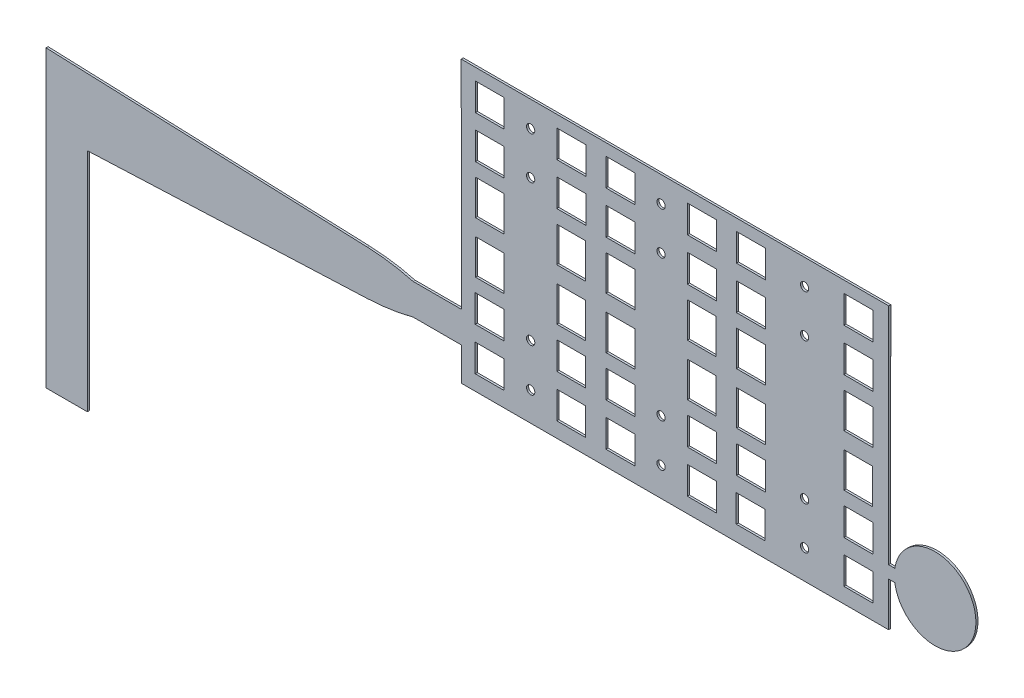
SolidWorks part; units mm, degrees
ref_plane "Alzado" through (0, 0, 0) normal (0, 0, 1) x (1, 0, 0)
ref_plane "Planta" through (0, 0, 0) normal (0, 1, 0) x (1, 0, 0)
ref_plane "Vista lateral" through (0, 0, 0) normal (1, 0, 0) x (0, 0, -1)
sketch "Model" plane through (0, 0, 0) normal (0, 0, 1) x (1, 0, 0)
  line L0 (63.6574, 52.8342) -> (70.6033, 52.8342)
  line L1 (83.3266, 52.8342) -> (90.3731, 52.8342)
  line L16 (63.6033, 8.4929) -> (63.6033, 1.862)
  line L18 (70.6033, 8.4929) -> (70.6033, 1.862)
  line L20 (63.6033, -1.862) -> (63.6033, -8.4929)
  line L22 (70.6033, -1.862) -> (70.6033, -8.4929)
  line L23 (114.8871, 52.902) -> (121.9188, 52.902)
  line L25 (90.3266, 8.4929) -> (90.3266, 1.862)
  line L27 (126.7514, 46.2379) -> (133.7301, 46.2379)
  line L31 (152.7437, 52.902) -> (159.7495, 52.902)
  line L32 (-40.1542, 7.8736) -> (-40.1542, -8.6736)
  line L33 (-40.1542, -8.6736) -> (-40.1542, -63.3381)
  line L35 (-40.1542, -63.3381) -> (-30.1542, -63.3381)
  line L36 (-30.1542, -63.3381) -> (-30.1542, -8.6736)
  line L38 (159.7495, 46.2379) -> (152.7437, 46.2379)
  line L39 (60.2582, -12.1607) -> (163.5406, -12.124)
  line L41 (83.3266, 8.4929) -> (83.3266, 1.862)
  line L43 (90.3266, -1.862) -> (90.3266, -8.4929)
  line L45 (83.3266, -1.862) -> (83.3266, -8.4929)
  line L47 (60.2286, 55.7055) -> (163.5735, 55.7055)
  line L48 (60.2286, 55.7055) -> (60.2582, 3.3361)
  line L49 (60.2582, -4.1361) -> (60.2582, -12.1607)
  line L50 (152.7437, 42.5548) -> (159.7495, 42.5548)
  line L51 (37.5383, -5.7873) -> (-30.1542, -8.6736)
  line L52 (-40.1542, 7.8736) -> (37.5383, 4.9873)
  line L53 (159.7495, 35.8907) -> (152.7437, 35.8907)
  line L54 (133.7301, 42.5548) -> (126.7354, 42.5548)
  line L55 (126.7354, 35.8907) -> (133.7301, 35.8907)
  line L56 (121.895, 35.9097) -> (114.8871, 35.9097)
  line L57 (114.8871, 42.5853) -> (121.895, 42.5853)
  line L58 (95.1895, 42.5853) -> (102.1795, 42.5853)
  line L59 (102.1795, 46.2074) -> (95.2023, 46.2074)
  line L60 (90.3731, 46.2049) -> (83.3266, 46.2049)
  line L61 (95.1795, 8.4893) -> (95.1795, 1.8233)
  line L63 (83.3266, 42.5878) -> (90.3731, 42.5878)
  line L64 (102.1795, 8.4893) -> (102.1795, 1.8233)
  line L66 (95.1795, -1.8233) -> (95.1795, -8.4893)
  line L68 (90.3731, 35.9585) -> (83.3266, 35.9585)
  line L69 (102.1795, -1.8233) -> (102.1795, -8.4893)
  line L71 (121.8871, -1.8233) -> (121.8871, -8.4893)
  line L73 (114.8871, -1.8233) -> (114.8871, -8.4893)
  line L75 (63.6574, 42.5878) -> (70.6033, 42.5878)
  line L76 (70.6033, 46.2049) -> (63.6574, 46.2049)
  line L77 (63.6033, 8.4929) -> (70.6033, 8.4929)
  line L78 (83.3266, 8.4929) -> (90.3266, 8.4929)
  line L79 (95.1795, 8.4893) -> (102.1795, 8.4893)
  line L80 (126.7301, 8.4673) -> (133.7301, 8.4673)
  line L81 (152.7437, 8.4673) -> (159.7437, 8.4673)
  line L82 (159.7437, 1.7882) -> (152.7437, 1.7882)
  line L83 (133.7301, 1.7882) -> (126.7301, 1.7882)
  line L84 (121.8871, 1.8233) -> (114.8871, 1.8233)
  line L85 (102.1795, 1.8233) -> (95.1795, 1.8233)
  line L86 (90.3266, 1.862) -> (83.3266, 1.862)
  line L87 (70.6033, 1.862) -> (63.6033, 1.862)
  line L88 (63.6033, -1.862) -> (70.6033, -1.862)
  line L89 (83.3266, -1.862) -> (90.3266, -1.862)
  line L91 (121.8871, 8.4893) -> (114.8871, 8.4893)
  line L92 (114.8871, 1.8233) -> (114.8871, 8.4893)
  line L94 (126.7301, 8.4673) -> (126.7301, 1.7882)
  line L99 (48.5942, 3.3361) -> (60.2582, 3.3361)
  line L100 (48.5942, -4.1361) -> (60.2582, -4.1361)
  line L101 (133.7301, 8.4673) -> (133.7301, 1.7882)
  line L113 (95.1795, -1.8233) -> (102.1795, -1.8233)
  line L114 (121.8871, 8.4893) -> (121.8871, 1.8233)
  line L123 (126.7038, -1.819) -> (126.7038, -8.4359)
  line L126 (159.729, -1.819) -> (159.729, -8.4359)
  line L128 (159.7437, 1.7882) -> (159.7437, 8.4673)
  line L132 (159.7495, 52.902) -> (159.7495, 46.2379)
  line L147 (133.7038, -1.819) -> (133.7038, -8.4359)
  line L151 (152.729, -8.4359) -> (152.729, -1.819)
  line L152 (114.8871, -1.8233) -> (121.8871, -1.8233)
  line L156 (152.7437, 1.7882) -> (152.7437, 8.4673)
  line L157 (126.7354, 52.902) -> (126.7354, 46.2379)
  line L159 (126.7354, 42.5548) -> (126.7354, 35.8907)
  line L161 (159.7495, 42.5548) -> (159.7495, 35.8907)
  line L164 (121.895, 35.9097) -> (121.895, 42.5853)
  line L166 (95.1895, 35.9097) -> (95.1895, 42.5853)
  line L168 (95.1895, 46.2074) -> (95.1895, 52.902)
  line L172 (63.6574, 52.8342) -> (63.6574, 46.2049)
  line L174 (70.6033, 52.8342) -> (70.6033, 46.2049)
  line L176 (63.6574, 42.5878) -> (63.6574, 35.9533)
  line L180 (90.3731, 52.8342) -> (90.3731, 46.2049)
  line L182 (90.3731, 42.5878) -> (90.3731, 35.9585)
  line L185 (63.6574, 35.9533) -> (70.6033, 35.9533)
  line L186 (70.6033, 42.5878) -> (70.6033, 35.9533)
  line L190 (83.3266, 35.9585) -> (83.3266, 42.5878)
  line L194 (126.7038, -1.819) -> (133.7038, -1.819)
  line L195 (83.3266, 46.2049) -> (83.3266, 52.8342)
  line L196 (95.2023, 52.8584) -> (102.1795, 52.8584)
  line L197 (95.2023, 52.8584) -> (95.2023, 46.2074)
  line L199 (102.1795, 52.8584) -> (102.1795, 46.2074)
  line L202 (95.1895, 35.9097) -> (102.1795, 35.9097)
  line L203 (152.729, -1.819) -> (159.729, -1.819)
  line L204 (102.1795, 42.5853) -> (102.1795, 35.9097)
  line L208 (114.8871, 35.9097) -> (114.8871, 42.5853)
  line L209 (121.9188, 46.2351) -> (114.8871, 46.2351)
  line L210 (121.9188, 46.2351) -> (121.9188, 52.902)
  line L212 (114.8871, 46.2351) -> (114.8871, 52.902)
  line L213 (126.7514, 52.8864) -> (133.7301, 52.8864)
  line L214 (126.7514, 52.8864) -> (126.7514, 46.2379)
  line L216 (133.7301, 52.8864) -> (133.7301, 46.2379)
  line L220 (133.7301, 42.5548) -> (133.7301, 35.8907)
  line L224 (152.7437, 35.8907) -> (152.7437, 42.5548)
  line L228 (152.7437, 46.2379) -> (152.7437, 52.902)
  line L229 (63.6719, 32.7054) -> (70.6033, 32.7054)
  line L230 (63.6719, 32.7054) -> (63.6719, 24.2109)
  line L231 (63.6719, 24.2109) -> (70.6033, 24.2109)
  line L232 (70.6033, 32.7054) -> (70.6033, 24.2109)
  line L233 (63.7086, 20.254) -> (70.6033, 20.254)
  line L234 (63.7086, 20.254) -> (63.7086, 11.7587)
  line L235 (63.7086, 11.7587) -> (70.6033, 11.7587)
  line L236 (70.6033, 20.254) -> (70.6033, 11.7587)
  line L237 (90.3114, 11.7467) -> (83.3266, 11.7467)
  line L238 (90.3114, 11.7467) -> (90.3114, 20.2401)
  line L239 (90.3114, 20.2401) -> (83.3266, 20.2401)
  line L240 (83.3266, 11.7467) -> (83.3266, 20.2401)
  line L241 (90.2656, 24.1969) -> (83.3266, 24.1969)
  line L242 (90.2656, 24.1969) -> (90.2656, 32.6894)
  line L243 (90.2656, 32.6894) -> (83.3266, 32.6894)
  line L244 (83.3266, 24.1969) -> (83.3266, 32.6894)
  line L245 (159.729, -8.4359) -> (152.729, -8.4359)
  line L246 (95.2169, 32.6805) -> (102.1795, 32.6805)
  line L247 (95.2169, 32.6805) -> (95.2169, 24.1873)
  line L248 (95.2169, 24.1873) -> (102.1795, 24.1873)
  line L249 (102.1795, 32.6805) -> (102.1795, 24.1873)
  line L250 (121.8739, 32.6569) -> (114.8871, 32.6569)
  line L251 (121.8739, 32.6569) -> (121.8739, 24.1766)
  line L252 (121.8739, 24.1766) -> (114.8871, 24.1766)
  line L253 (114.8871, 32.6569) -> (114.8871, 24.1766)
  line L254 (121.813, 20.2091) -> (114.8871, 20.2091)
  line L255 (121.813, 20.2091) -> (121.813, 11.729)
  line L256 (121.813, 11.729) -> (114.8871, 11.729)
  line L257 (114.8871, 20.2091) -> (114.8871, 11.729)
  line L258 (95.2605, 20.2314) -> (102.1795, 20.2314)
  line L259 (95.2605, 20.2314) -> (95.2605, 11.7381)
  line L260 (95.2605, 11.7381) -> (102.1795, 11.7381)
  line L261 (102.1795, 20.2314) -> (102.1795, 11.7381)
  line L262 (126.8116, 20.2054) -> (133.7301, 20.2054)
  line L263 (126.8116, 20.2054) -> (126.8116, 11.7157)
  line L264 (126.8116, 11.7157) -> (133.7301, 11.7157)
  line L268 (133.7301, 20.2054) -> (133.7301, 11.7157)
  line L269 (126.7675, 32.6533) -> (133.7301, 32.6533)
  line L270 (126.7675, 32.6533) -> (126.7675, 24.1624)
  line L271 (126.7675, 24.1624) -> (133.7301, 24.1624)
  line L272 (133.7301, 32.6533) -> (133.7301, 24.1624)
  line L273 (159.7336, 32.6369) -> (152.7437, 32.6369)
  line L274 (159.7336, 32.6369) -> (159.7336, 24.1492)
  line L275 (159.7336, 24.1492) -> (152.7437, 24.1492)
  line L276 (152.7437, 32.6369) -> (152.7437, 24.1492)
  line L277 (159.6767, 20.1824) -> (152.7437, 20.1824)
  line L278 (159.6767, 20.1824) -> (159.6767, 11.7002)
  line L279 (159.6767, 11.7002) -> (152.7437, 11.7002)
  line L280 (152.7437, 20.1824) -> (152.7437, 11.7002)
  line L281 (133.7038, -8.4359) -> (126.7038, -8.4359)
  line L282 (121.8871, -8.4893) -> (114.8871, -8.4893)
  line L283 (102.1795, -8.4893) -> (95.1795, -8.4893)
  line L284 (70.6033, -8.4929) -> (63.6033, -8.4929)
  line L285 (83.3266, -8.4929) -> (90.3266, -8.4929)
  line L286 (174.7965, 0) -> (163.5465, 0)
  line L287 (163.5465, 1.5) -> (165.0465, 1.5)
  line L288 (163.5465, -1.5) -> (165.0465, -1.5)
  line L289 (163.5465, -1.5) -> (163.5406, -12.124)
  line L290 (163.5735, 55.7055) -> (163.5465, 1.5)
  circle A0 centre (77.0152, 39.2732) radius 1
  circle A1 centre (77.0152, 49.5195) radius 1
  circle A2 centre (108.5423, 49.5195) radius 1
  circle A3 centre (108.5423, 39.2732) radius 1
  circle A4 centre (143.2425, 39.2732) radius 1
  circle A5 centre (143.2425, 49.57) radius 1
  circle A6 centre (77.0152, 5.1774) radius 1
  circle A7 centre (108.5423, 5.1563) radius 1
  circle A8 centre (143.2441, 5.1277) radius 1
  circle A9 centre (77.0152, -5.1774) radius 1
  circle A10 centre (108.5423, -5.1774) radius 1
  circle A11 centre (143.2441, -5.1275) radius 1
  arc A14 (165.0465, 1.5) -> (165.0441, -1.4843) centre (174.7965, 0) cw
  spline S10 degree 3 poles (48.5942, 3.3361) (48.3679, 3.3933) (47.9155, 3.5076) (47.2357, 3.6746) (46.5536, 3.8322) (45.8688, 3.9775) (45.1819, 4.1124) (44.2637, 4.2804) (43.1121, 4.468) (42.0326, 4.6121) (41.1055, 4.72) (40.4092, 4.7925) (39.6344, 4.8603) (38.9361, 4.9099) (38.2373, 4.9507) (37.7713, 4.9751) (37.5383, 4.9873) knots 0 0 0 0 0.062504 0.125003 0.187497 0.249996 0.312502 0.375006 0.500003 0.625001 0.66667 0.750008 0.812508 0.875003 0.937501 1 1 1 1
  spline S39 degree 3 poles (48.5942, -4.1361) (48.3679, -4.1933) (47.9155, -4.3076) (47.2357, -4.4746) (46.5536, -4.6322) (45.8688, -4.7775) (45.1819, -4.9124) (44.2637, -5.0804) (43.1121, -5.268) (42.0326, -5.4121) (41.1055, -5.52) (40.4092, -5.5925) (39.6344, -5.6603) (38.9361, -5.7099) (38.2373, -5.7507) (37.7713, -5.7751) (37.5383, -5.7873) knots 0 0 0 0 0.062504 0.125003 0.187497 0.249996 0.312502 0.375006 0.500003 0.625001 0.66667 0.750008 0.812508 0.875003 0.937501 1 1 1 1
  dimension "D1" = 2
  dimension "D2" = 7
  dimension "D3" = 10
  dimension "D4" = 7
  dimension "D5" = 7
  dimension "D6" = 11.25
  dimension "D7" = 7
  dimension "D8" = 7
  dimension "D9" = 7
  dimension "D10" = 1.5
  dimension "D11" = 1.5
  dimension "D12" = 7
  dimension "D13" = 1.5
  dimension "D14" = 1.5
extrude "Saliente-Extruir1" add sketch "Model" along normal blind 0.5
